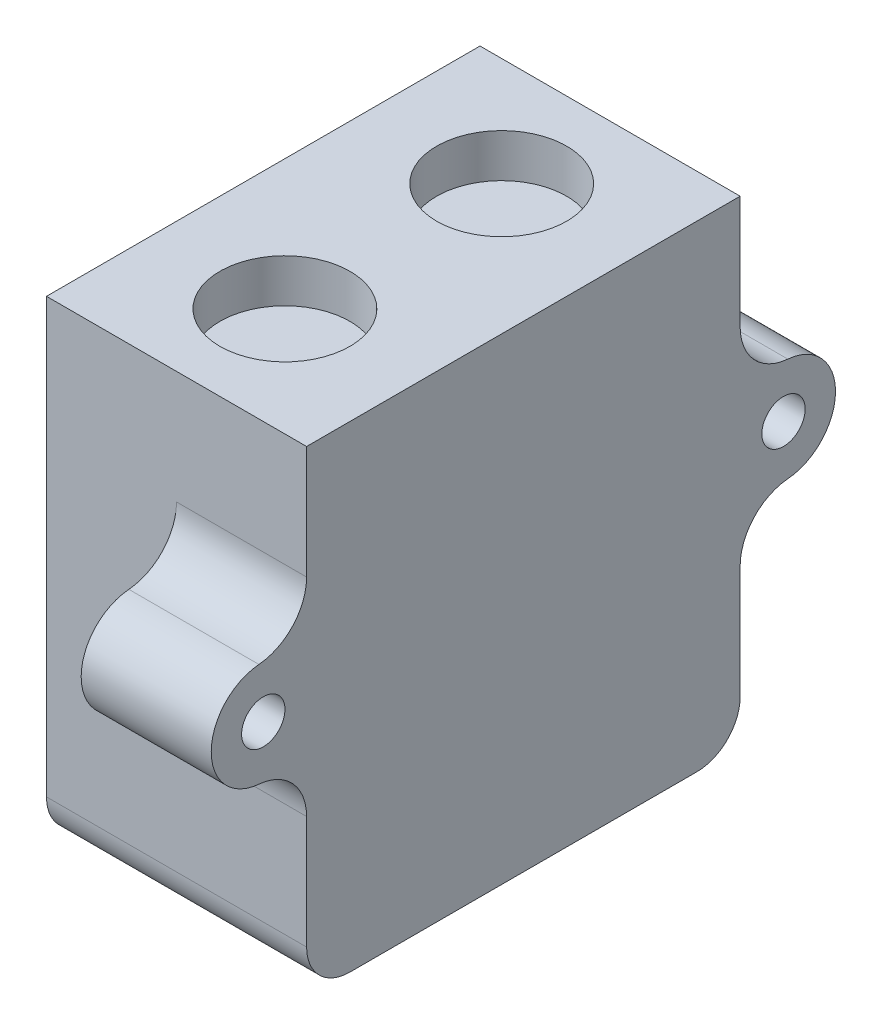
SolidWorks part; units mm, degrees
material "7075-T6 (SN)"
ref_plane "Front Plane" through (0, 0, 0) normal (0, 0, 1) x (1, 0, 0)
ref_plane "Top Plane" through (0, 0, 0) normal (0, 1, 0) x (1, 0, 0)
ref_plane "Right Plane" through (0, 0, 0) normal (1, 0, 0) x (0, 0, -1)
sketch "Sketch2" plane through (0, 0, 0) normal (1, 0, 0) x (0, 0, -1)
  line L2 (-50, 50) -> (-50, -50)
  line L3 (-50, -50) -> (50, -50)
  line L4 (50, 50) -> (50, -50)
  line L7 (-50, 50) -> (50, 50)
  point P5 (0, -50)
  point P9 (-50, 0)
  dimension "D1" = 100
  dimension "D3" = 100
extrude "Boss-Extrude1" add sketch "Sketch2" along normal blind 60
sketch "Sketch3" plane through (0, 0, 0) normal (-1, 0, 0) x (0, 0, 1)
  circle A0 centre (0, 0) radius 31
  dimension "D1" = 62
extrude "Cut-Extrude1" cut sketch "Sketch3" against normal blind 30
fillet "Fillet1" radius 10 2 edges at (30, -50, 50) (30, -50, -50)
sketch "Sketch4" plane through (0, 50, 0) normal (0, 1, 0) x (1, 0, 0)
  line L0 (60, -50) -> (0, -50) construction
  line L2 (60, 50) -> (0, 50) construction
  line L3 (60, 50) -> (60, -50) construction
  line L4 (0, 50) -> (0, -50) construction
  line L5 (60, 50) -> (0, 50)
  line L6 (60, 50) -> (60, -50)
  line L7 (60, -50) -> (0, -50)
  line L8 (0, 50) -> (0, -50)
  circle A0 centre (30, 25) radius 15
  circle A1 centre (30, -25) radius 15
  point P4 (0, 0)
  point P7 (30, -50)
  dimension "D1" = 30
  dimension "D2" = 50
  dimension "D3" = 25
extrude "Boss-Extrude2" add sketch "Sketch4" along normal blind 10
sketch "Sketch6" plane through (60, 0, 0) normal (1, 0, 0) x (0, 0, -1)
  line L0 (-50, 60) -> (-50, -40) construction
  line L1 (-50, 33.9165) -> (-50, -13.9165)
  arc A0 (-50, -13.9165) -> (-61, -1.9583) centre (-62, -13.9165) ccw
  arc A1 (-61, -1.9583) -> (-61, 21.9583) centre (-60, 10) cw
  arc A2 (-61, 21.9583) -> (-50, 33.9165) centre (-62, 33.9165) ccw
  circle A3 centre (-60, 10) radius 5
  point P11 (-50, 10)
  point P12 (-50, 10)
  dimension "D1" = 12
  dimension "D2" = 10
  dimension "D3" = 10
extrude "Boss-Extrude3" add sketch "Sketch6" against normal blind 30
ref_plane "Plane1" through (0, 0, 0) normal (0, 0, -1) x (-1, 0, 0)
mirror "Mirror1" about plane through (0, 0, 0) normal (0, 0, -1) of "Boss-Extrude3"
